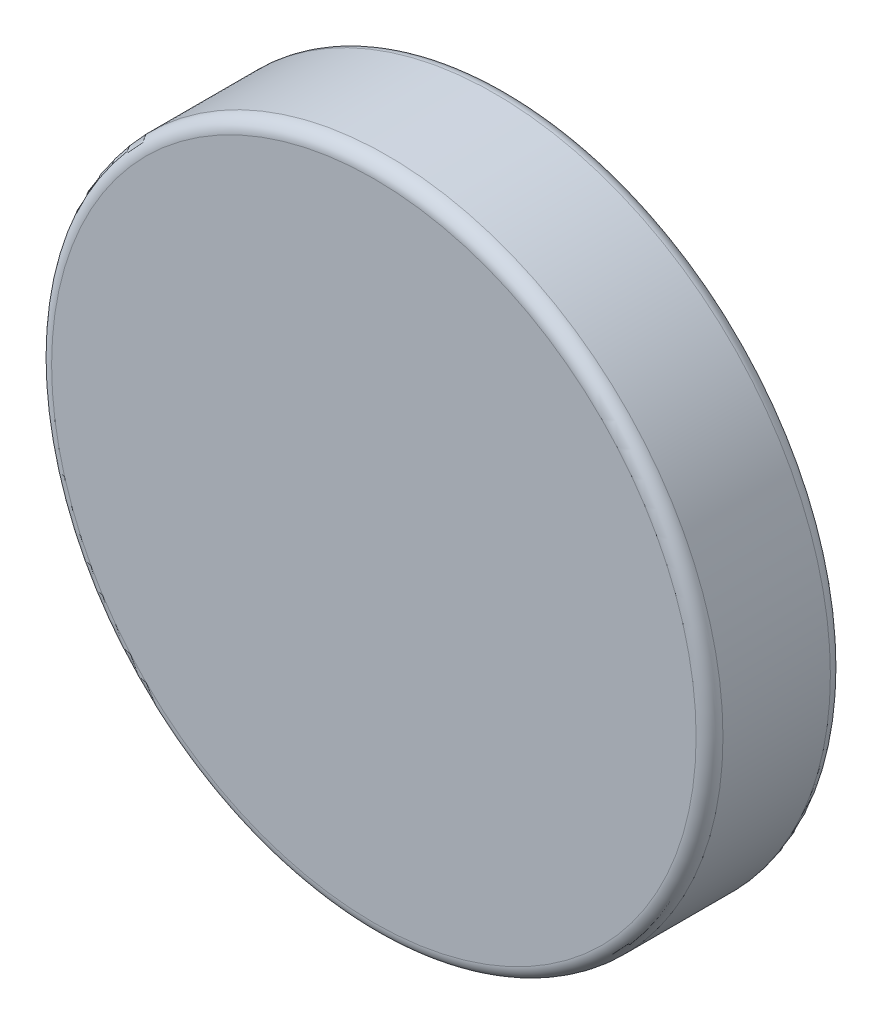
SolidWorks part; units mm, degrees
ref_plane "前视基准面" through (0, 0, 0) normal (0, 0, 1) x (1, 0, 0)
ref_plane "上视基准面" through (0, 0, 0) normal (0, 1, 0) x (1, 0, 0)
ref_plane "右视基准面" through (0, 0, 0) normal (1, 0, 0) x (0, 0, -1)
sketch "草图1" plane through (0, 0, 0) normal (0, 0, 1) x (1, 0, 0)
  circle A0 centre (0, 0) radius 5
extrude "凸台-拉伸1" add sketch "草图1" along normal blind 2
fillet "圆角1" radius 0.2 2 edges at (5, 0, 0) (5, 0, 2)
